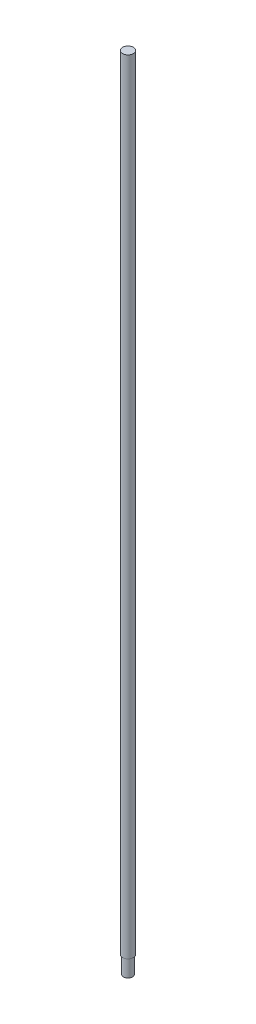
SolidWorks part; units mm, degrees
ref_plane "Alzado" through (0, 0, 0) normal (0, 0, 1) x (1, 0, 0)
ref_plane "Planta" through (0, 0, 0) normal (0, 1, 0) x (1, 0, 0)
ref_plane "Vista lateral" through (0, 0, 0) normal (1, 0, 0) x (0, 0, -1)
sketch "Croquis1" plane through (0, 0, 0) normal (0, 1, 0) x (1, 0, 0)
  circle A0 centre (0, 0) radius 4.7625
  dimension "D1" = 9.525
extrude "Saliente-Extruir1" add sketch "Croquis1" along normal blind 685
sketch "Croquis2" plane through (0, 0, 0) normal (0, -1, 0) x (1, 0, 0)
  circle A0 centre (0, 0) radius 4
  dimension "D1" = 8
extrude "Saliente-Extruir2" add sketch "Croquis2" along normal blind 15
sketch "Croquis3" plane through (0, 685, 0) normal (0, 1, 0) x (1, 0, 0)
  line L0 (4.7625, 0) -> (-4.7625, 0) construction
  circle A0 centre (0, 0) radius 4.7625 construction
